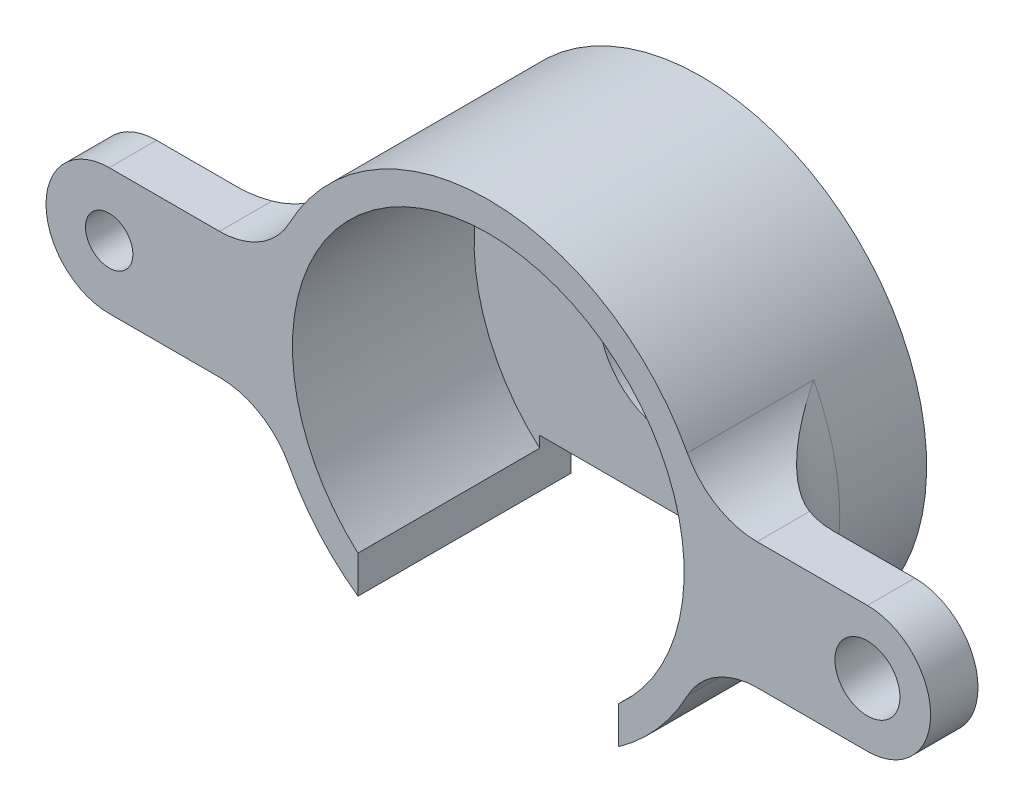
SolidWorks part; units mm, degrees
ref_plane "前视基准面" through (0, 0, 0) normal (0, 0, 1) x (1, 0, 0)
ref_plane "上视基准面" through (0, 0, 0) normal (0, 1, 0) x (1, 0, 0)
ref_plane "右视基准面" through (0, 0, 0) normal (1, 0, 0) x (0, 0, -1)
other "Configuration Table"
sketch "草图1" plane through (0, 0, 0) normal (0, 0, 1) x (1, 0, 0)
  circle A0 centre (0, 0) radius 12.4
  circle A1 centre (0, 0) radius 14.25
  dimension "D1" = 24.8
  dimension "D2" = 28.5
extrude "凸台-拉伸1" add sketch "草图1" along normal blind 11.5
sketch "草图2" plane through (0, 0, 0) normal (0, 0, -1) x (-1, 0, 0)
  line L0 (0, 0) -> (-10, 0)
  circle A0 centre (0, 0) radius 14.25
  circle A1 centre (0, 0) radius 4.5
  circle A2 centre (-10, 0) radius 1.5
  dimension "D1" = 9
  dimension "D3" = 3
  dimension "D2" = 10
extrude "凸台-拉伸2" add sketch "草图2" along normal blind 2
sketch "草图4" plane through (0, 0, 11.5) normal (0, 0, 1) x (1, 0, 0)
  line L1 (-8.25, -16.2559) -> (8.25, -16.2559)
  line L2 (-8.25, -16.2559) -> (-8.25, -8.5441)
  line L3 (-8.25, -8.5441) -> (8.25, -8.5441)
  line L4 (8.25, -16.2559) -> (8.25, -8.5441)
  line L5 (-8.25, -16.2559) -> (8.25, -8.5441) construction
  line L6 (-8.25, -8.5441) -> (8.25, -16.2559) construction
  circle A0 centre (0, 0) radius 12.4 construction
  circle A1 centre (0, 0) radius 12.4 construction
  point P0 (0, -12.4)
  dimension "D1" = 16.5
extrude "切除-拉伸2" cut sketch "草图4" against normal blind 19
sketch "草图5" plane through (0, 0, 11.5) normal (0, 0, 1) x (1, 0, 0)
  line L0 (0, 0) -> (-24, 0) construction
  line L1 (-24, 0) -> (24, 0) construction
  line L2 (-24, 4) -> (-13.6771, 4)
  line L3 (-24, -4) -> (-13.6771, -4)
  line L4 (13.6771, 4) -> (24, 4)
  line L5 (13.6771, -4) -> (24, -4)
  arc A0 (-24, 4) -> (-24, -4) centre (-24, 0) ccw
  arc A1 (24, -4) -> (24, 4) centre (24, 0) ccw
  circle A2 centre (-24, 0) radius 1.5
  circle A3 centre (24, 0) radius 2.0584
  arc A4 (-13.6771, 4) -> (-13.6771, -4) centre (0, 0) ccw
  arc A5 (13.6771, -4) -> (13.6771, 4) centre (0, 0) ccw
  point P3 (0, 0)
  dimension "D2" = 4
  dimension "D4" = 3
  dimension "D1" = 24
  dimension "D3" = 48
extrude "凸台-拉伸3" add sketch "草图5" against normal blind 3 contours L2 A4 L3 A0 | L4 A1 L5 A5 | A2 | A3
fillet "圆角1" radius 5 6 edges at (-13.6771, -4, 10) (-14.25, 0, 8.5) (-13.6771, 4, 10) (13.6771, 4, 10) (14.25, 0, 8.5) (13.6771, -4, 10)
